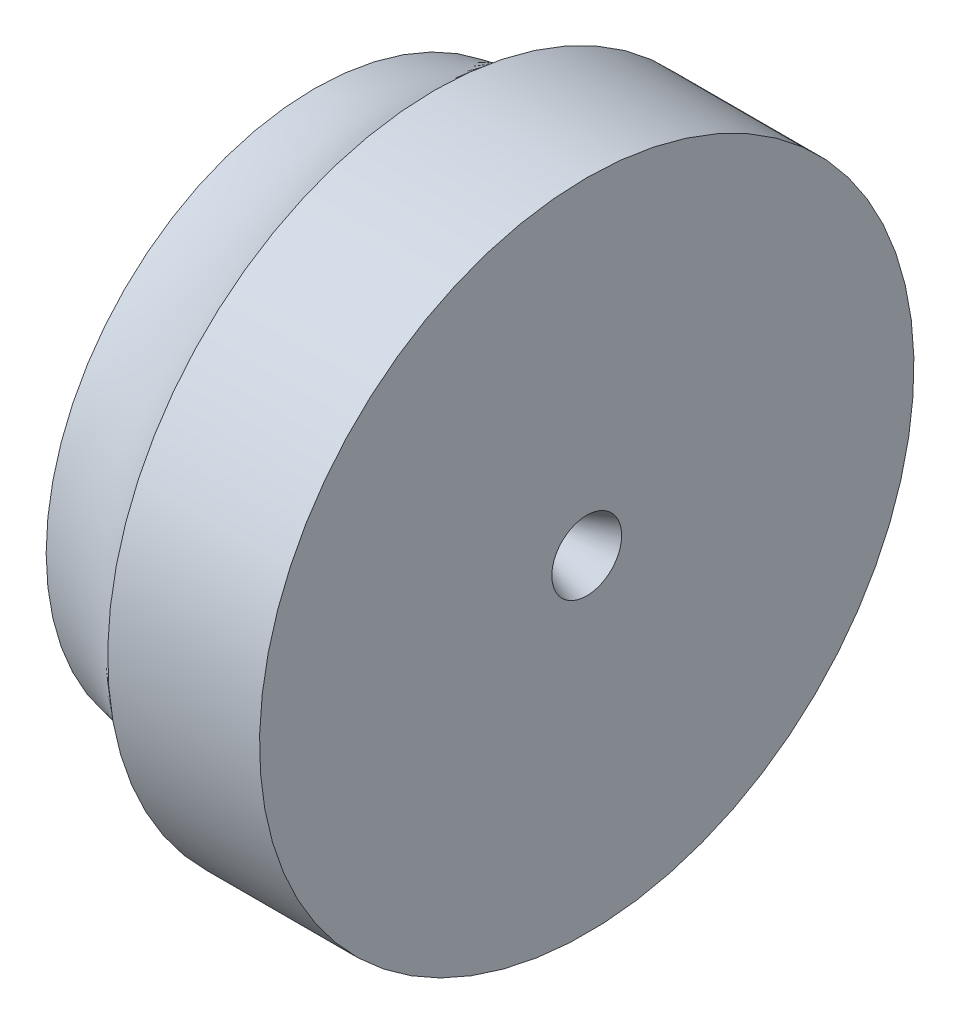
SolidWorks part; units mm, degrees
ref_plane "Front" through (0, 0, 0) normal (0, 0, 1) x (1, 0, 0)
ref_plane "Top" through (0, 0, 0) normal (0, 1, 0) x (1, 0, 0)
ref_plane "Right" through (0, 0, 0) normal (1, 0, 0) x (0, 0, -1)
sketch "Sketch2" plane through (0, 0, 0) normal (0, 0, 1) x (1, 0, 0)
  line L0 (0, 0) -> (0, 14.55)
  line L1 (0, 14.55) -> (-16.2, 30.75)
  line L2 (-2.4, 37.5) -> (15, 37.5)
  line L3 (15, 37.5) -> (15, 4)
  line L4 (15, 4) -> (5, 0)
  line L5 (5, 0) -> (0, 0)
  arc A0 (-16.2, 30.75) -> (-2.4, 37.5) centre (-19.7533, 55.4962) ccw
  dimension "D4" = 25
  dimension "D1" = 135
  dimension "D2" = 14.55
  dimension "D3" = 30.75
  dimension "D5" = 13.8
  dimension "D6" = 15
  dimension "D7" = 37.5
  dimension "D8" = 4
  dimension "D9" = 10
revolve "Revolve1" add sketch "Sketch2" angle 360 about L5
